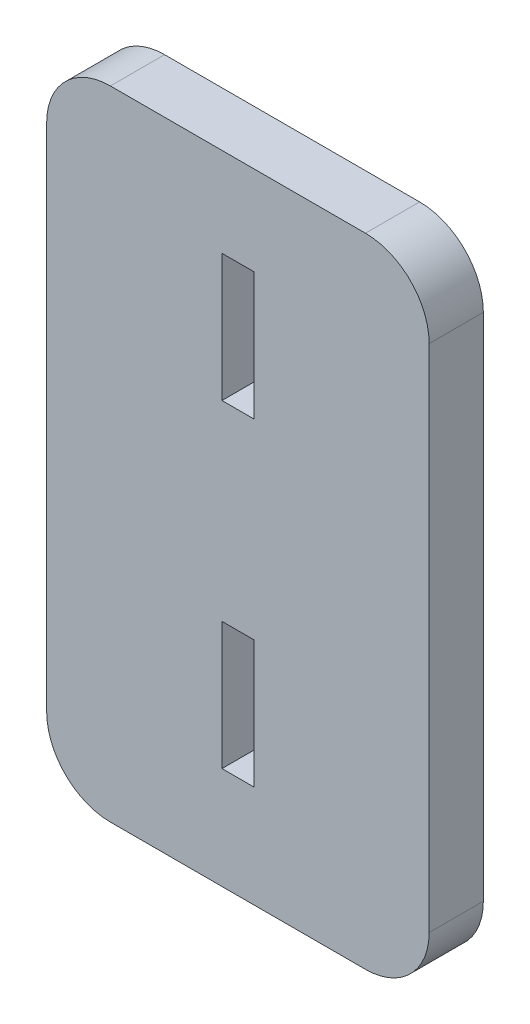
SolidWorks part; units mm, degrees
ref_plane "Alzado" through (0, 0, 0) normal (0, 0, 1) x (1, 0, 0)
ref_plane "Planta" through (0, 0, 0) normal (0, 1, 0) x (1, 0, 0)
ref_plane "Vista lateral" through (0, 0, 0) normal (1, 0, 0) x (0, 0, -1)
sketch "Croquis2" plane through (0, 0, 0) normal (0, 0, 1) x (1, 0, 0)
  line L0 (50, 50) -> (50, -50) construction
  line L1 (-30, 50) -> (30, 50)
  line L2 (-30, 50) -> (-30, -50)
  line L3 (-30, -50) -> (30, -50)
  line L4 (30, 50) -> (30, -50)
  line L5 (-30, 50) -> (30, -50) construction
  line L6 (-30, -50) -> (30, 50) construction
  line L7 (0, 50) -> (0, -50) construction
  line L8 (-50, 50) -> (-50, -50) construction
  point P0 (0, 0)
  dimension "D1" = 100
  dimension "D2" = 60
  dimension "D3" = 80
  dimension "D4" = 80
extrude "Saliente-Extruir1" add sketch "Croquis2" along normal blind 8.5
ref_plane "Plano1" through (0, 0, 8.5) normal (0, 0, 1) x (1, 0, 0)
sketch "Croquis4" plane through (0, 0, 8.5) normal (0, 0, 1) x (1, 0, 0)
  line L0 (0, 50) -> (0, -50) construction
  line L1 (30, 50) -> (-30, 50) construction
  line L2 (-30, -50) -> (30, -50) construction
  line L4 (-30, 50) -> (-30, -50) construction
  line L5 (30, -50) -> (30, 50) construction
  line L6 (-30, 0) -> (30, 0) construction
  line L8 (-2.5, 36.02) -> (2.5, 36.02)
  line L9 (-2.5, 36.02) -> (-2.5, 16.02)
  line L10 (-2.5, 16.02) -> (2.5, 16.02)
  line L11 (2.5, 36.02) -> (2.5, 16.02)
  line L12 (-2.5, 36.02) -> (2.5, 16.02) construction
  line L13 (-2.5, 16.02) -> (2.5, 36.02) construction
  line L14 (-2.5, -13.98) -> (2.5, -13.98)
  line L15 (-2.5, -13.98) -> (-2.5, -33.98)
  line L16 (-2.5, -33.98) -> (2.5, -33.98)
  line L17 (2.5, -13.98) -> (2.5, -33.98)
  line L18 (-2.5, -13.98) -> (2.5, -33.98) construction
  line L19 (-2.5, -33.98) -> (2.5, -13.98) construction
  point P14 (0, 26.02)
  point P19 (0, -23.98)
  point P24 (8, 40)
  point P29 (8, -40)
  dimension "D1" = 23.98
  dimension "D2" = 26.02
  dimension "D3" = 5
  dimension "D4" = 20
  dimension "D7" = 5
  dimension "D8" = 20
extrude "Cortar-Extruir1" cut sketch "Croquis4" against normal blind 7.48
fillet "Redondeo1" radius 10 1 edges at (-30, 50, 4.25)
fillet "Redondeo2" radius 10 3 edges at (30, -50, 4.25) (-30, -50, 4.25) (30, 50, 4.25)
